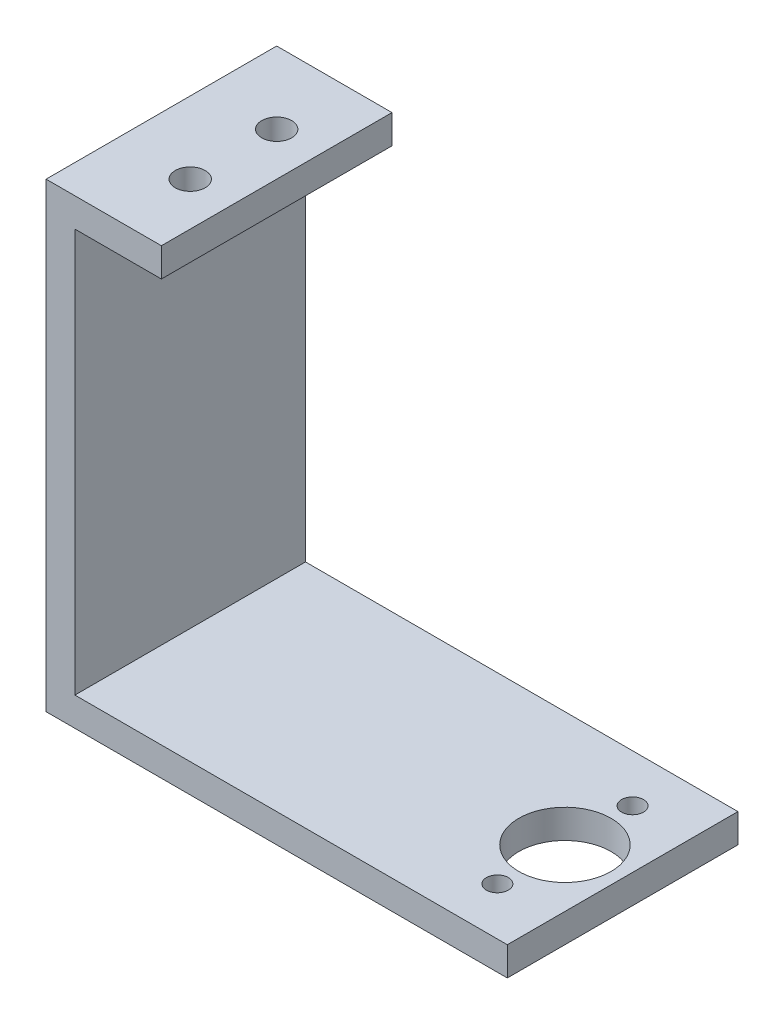
SolidWorks part; units mm, degrees
ref_plane "Front Plane" through (0, 0, 0) normal (0, 0, 1) x (1, 0, 0)
ref_plane "Top Plane" through (0, 0, 0) normal (0, 1, 0) x (1, 0, 0)
ref_plane "Right Plane" through (0, 0, 0) normal (1, 0, 0) x (0, 0, -1)
sketch "Sketch1" plane through (0, 0, 0) normal (0, 0, 1) x (1, 0, 0)
  line L0 (-17.0593, 26.9872) -> (-29.7593, 26.9872)
  line L1 (-29.7593, 26.9872) -> (-29.7593, -23.8128)
  line L2 (-29.7593, -23.8128) -> (21.0407, -23.8128)
  line L3 (-17.0593, 23.8122) -> (-26.5843, 23.8122)
  line L4 (-26.5843, 23.8122) -> (-26.5843, -20.6378)
  line L5 (-26.5843, -20.6378) -> (21.0407, -20.6378)
  line L6 (-17.0593, 26.9872) -> (-17.0593, 23.8122)
  line L7 (21.0407, -23.8128) -> (21.0407, -20.6378)
  dimension "D2" = 12.7
  dimension "D3" = 50.8
  dimension "D4" = 50.8
  dimension "D1" = 3.175
extrude "Boss-Extrude1" add sketch "Sketch1" along normal blind 25.4
hole_wizard "M4x0.7 Tapped Hole1" positions "Sketch6" profile "Sketch5" tap size "M4x0.7" standard "ANSI Metric"
sketch "Sketch6" plane through (0, 26.9872, 0) normal (0, 1, 0) x (1, 0, 0)
  line L1 (-17.0593, -25.4) -> (-17.0593, 0) construction
  line L2 (-17.0593, 0) -> (-29.7593, 0) construction
  point P0 (-21.8218, -7.9375)
  point P2 (-21.8218, -17.4625)
  dimension "D1" = 4.7625
  dimension "D2" = 9.525
  dimension "D3" = 7.9375
sketch "Sketch5" plane through (-21.8218, 26.9872, 7.9375) normal (1, 0, 0) x (0, 0, 1)
  line L0 (0, 0) -> (0, 10.8974)
  line L1 (0, 10.8974) -> (1.65, 9.906)
  line L2 (1.65, 9.906) -> (1.65, 0)
  line L5 (1.65, 0) -> (0, 0)
  line L10 (0, 10.8974) -> (-1.65, 9.906) construction
  line L11 (0, -6.35) -> (0, 107.95) construction
  dimension "Tap Drill Dia." = 3.3
  dimension "Tap Drill Depth" = 9.906
  dimension "Drill Angle" = 118
sketch "Sketch7" plane through (0, -23.8128, 0) normal (0, -1, 0) x (1, 0, 0)
  line L0 (-29.7593, 25.4) -> (21.0407, 25.4) construction
  line L1 (21.0407, 25.4) -> (21.0407, 0) construction
  circle A0 centre (14.6907, 12.7) radius 5.08
  circle A1 centre (14.6907, 12.7) radius 7.4422 construction
  circle A2 centre (14.6907, 5.2578) radius 1.2065
  circle A3 centre (14.6907, 20.1422) radius 1.2065
  dimension "D3" = 10.16
  dimension "D4" = 14.8844
  dimension "D5" = 2.413
  dimension "D1" = 12.7
  dimension "D2" = 6.35
extrude "Cut-Extrude1" cut sketch "Sketch7" against normal up to next
